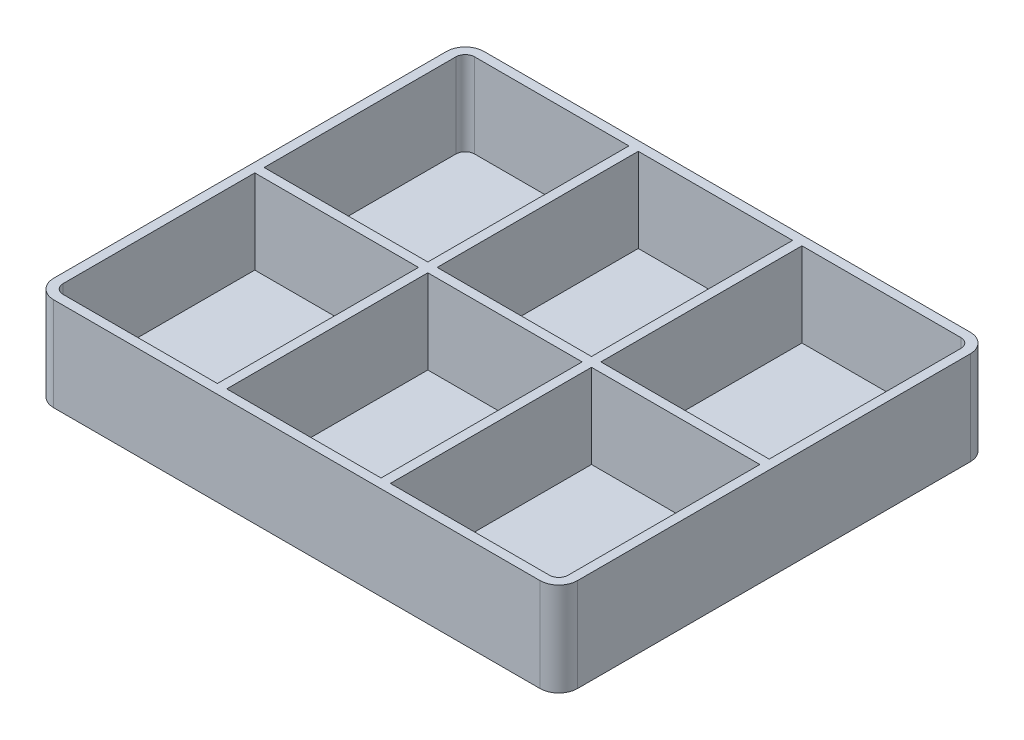
SolidWorks part; units mm, degrees
ref_plane "정면" through (0, 0, 0) normal (0, 0, 1) x (1, 0, 0)
ref_plane "윗면" through (0, 0, 0) normal (0, 1, 0) x (1, 0, 0)
ref_plane "우측면" through (0, 0, 0) normal (1, 0, 0) x (0, 0, -1)
sketch "스케치1" plane through (0, 0, 0) normal (0, 1, 0) x (1, 0, 0)
  line L1 (10, 0) -> (270, 0)
  line L2 (0, 10) -> (0, 220)
  line L3 (10, 230) -> (270, 230)
  line L4 (280, 10) -> (280, 220)
  arc A0 (270, 230) -> (280, 220) centre (270, 220) cw
  arc A1 (270, 0) -> (280, 10) centre (270, 10) ccw
  arc A2 (10, 0) -> (0, 10) centre (10, 10) cw
  arc A3 (0, 220) -> (10, 230) centre (10, 220) cw
  point P9 (280, 0)
  point P12 (0, 0)
  point P15 (0, 230)
  dimension "D3" = 10
  dimension "D1" = 280
  dimension "D2" = 230
extrude "보스-돌출1" add sketch "스케치1" along normal blind 50
shell "쉘1" thickness 5
sketch "스케치4" plane through (0, 5, 0) normal (0, 1, 0) x (1, 0, 0)
  line L0 (95, 225) -> (95, 5) construction
  line L1 (270, 225) -> (10, 225) construction
  line L2 (10, 5) -> (270, 5) construction
  line L3 (5, 220) -> (5, 10)
  line L4 (270, 225) -> (10, 225) construction
  line L5 (185, 225) -> (180, 5) construction
  line L6 (185, 5) -> (180, 225) construction
  line L7 (140, 225) -> (140, 5) construction
  line L8 (5, 220) -> (5, 10) construction
  line L9 (180, 5) -> (180, 225)
  line L10 (92.5, 5) -> (97.5, 5)
  line L11 (92.5, 5) -> (92.5, 225)
  line L12 (92.5, 225) -> (97.5, 225)
  line L13 (97.5, 5) -> (97.5, 225)
  line L14 (92.5, 5) -> (97.5, 225) construction
  line L15 (92.5, 225) -> (97.5, 5) construction
  line L16 (185, 5) -> (185, 225)
  line L17 (185, 5) -> (180, 5)
  line L18 (185, 225) -> (180, 225)
  line L19 (5, 115) -> (275, 115) construction
  line L20 (5, 220) -> (5, 10) construction
  line L21 (275, 10) -> (275, 220) construction
  line L22 (275, 10) -> (275, 220) construction
  line L23 (5, 117.5) -> (275, 117.5)
  line L24 (5, 117.5) -> (5, 112.5)
  line L25 (5, 112.5) -> (275, 112.5)
  line L26 (275, 117.5) -> (275, 112.5)
  line L27 (5, 117.5) -> (275, 112.5) construction
  line L28 (5, 112.5) -> (275, 117.5) construction
  line L34 (10, 5) -> (270, 5) construction
  line L37 (270, 230) -> (10, 230)
  line L38 (0, 220) -> (0, 10)
  line L39 (10, 0) -> (270, 0)
  line L40 (280, 10) -> (280, 220)
  line L41 (270, 230) -> (10, 230)
  line L42 (0, 220) -> (0, 10)
  line L43 (10, 0) -> (270, 0)
  line L44 (280, 10) -> (280, 220)
  arc A4 (280, 220) -> (270, 230) centre (270, 220) ccw
  arc A5 (10, 230) -> (0, 220) centre (10, 220) ccw
  arc A6 (0, 10) -> (10, 0) centre (10, 10) ccw
  arc A7 (270, 0) -> (280, 10) centre (270, 10) ccw
  arc A8 (280, 220) -> (270, 230) centre (270, 220) ccw
  arc A9 (10, 230) -> (0, 220) centre (10, 220) ccw
  arc A10 (0, 10) -> (10, 0) centre (10, 10) ccw
  arc A11 (270, 0) -> (280, 10) centre (270, 10) ccw
  point P6 (185, 225)
  point P10 (95, 115)
  point P30 (140, 115)
  point P36 (140, 115)
  point P44 (140, 225)
  point P49 (140, 5)
  point P52 (185, 5)
  point P57 (180, 5)
  point P58 (180, 225)
  point P59 (180, 225)
  point P60 (275, 115)
  point P61 (0, 0)
  point P62 (0, 0)
  dimension "D1" = 90
  dimension "D2" = 5
  dimension "D3" = 5
  dimension "D5" = 0
  dimension "D6" = 90
  dimension "D7" = 5
extrude "보스-돌출3" add sketch "스케치4" along normal blind 45 contours L9 L23 L16 L10 | L25 L9 L4 L16 | L9 L25 L16 L23
sketch "스케치5" plane through (0, 5, 0) normal (0, 1, 0) x (1, 0, 0)
  line L5 (5, 112.5) -> (92.5, 112.5) construction
  line L8 (34.2121, 5) -> (57.3472, 5)
  line L9 (10, 5) -> (92.5, 5) construction
  line L11 (5, 112.5) -> (5, 10) construction
  line L12 (5, 93.75) -> (92.5, 93.75)
  line L13 (5, 93.75) -> (5, 98.75)
  line L14 (5, 98.75) -> (92.5, 98.75)
  line L15 (92.5, 93.75) -> (92.5, 98.75)
  line L16 (92.5, 5) -> (92.5, 112.5) construction
  dimension "D1" = 5
  dimension "D2" = 13.75
